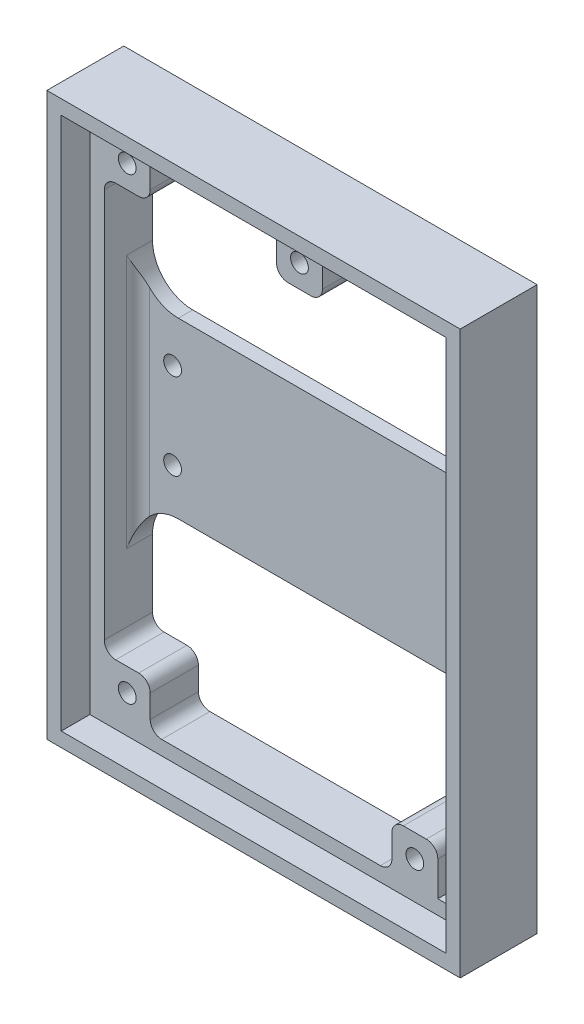
SolidWorks part; units mm, degrees
ref_plane "Plan de face" through (0, 0, 0) normal (0, 0, 1) x (1, 0, 0)
ref_plane "Plan de dessus" through (0, 0, 0) normal (0, 1, 0) x (1, 0, 0)
ref_plane "Plan de droite" through (0, 0, 0) normal (1, 0, 0) x (0, 0, -1)
sketch "Esquisse1" plane through (0, 0, 0) normal (0, 0, 1) x (1, 0, 0)
  line L0 (43, -39.95) -> (35.1, -39.95) construction
  line L1 (-15, 39.95) -> (15, 39.95) construction
  line L2 (-15, 39.95) -> (-15, -39.95) construction
  line L3 (-15, -39.95) -> (15, -39.95) construction
  line L4 (15, 39.95) -> (15, -39.95) construction
  line L5 (-15, 39.95) -> (15, -39.95) construction
  line L6 (-15, -39.95) -> (15, 39.95) construction
  line L11 (-19, 43.75) -> (43, 43.75) construction
  line L13 (-19, 43.75) -> (-19, -44.35) construction
  line L14 (-19, -44.35) -> (43, -44.35) construction
  line L15 (43, 43.75) -> (43, -44.35) construction
  line L16 (-19, 35.95) -> (-11, 35.95)
  line L17 (-11, 35.95) -> (-11, 43.95)
  line L18 (-11, 43.95) -> (11, 43.95)
  line L19 (11, 43.95) -> (11, 35.95)
  line L20 (11, 35.95) -> (19, 35.95)
  line L21 (19, 35.95) -> (19, 43.95)
  line L22 (19, 43.95) -> (43, 43.95)
  line L23 (43, 43.95) -> (43, -43.95)
  line L24 (43, -43.95) -> (39.1, -43.95)
  line L25 (39.1, -43.95) -> (39.1, -35.95)
  line L26 (39.1, -35.95) -> (31.1, -35.95)
  line L27 (31.1, -35.95) -> (31.1, -43.95)
  line L28 (31.1, -43.95) -> (-11, -43.95)
  line L29 (-11, -43.95) -> (-11, -35.95)
  line L30 (-11, -35.95) -> (-19, -35.95)
  line L31 (-19, -35.95) -> (-19, 35.95)
  line L32 (-24, 0) -> (-19, 0) construction
  line L33 (-24, 48.95) -> (48, 48.95)
  line L34 (-24, 48.95) -> (-24, -48.95)
  line L35 (-24, -48.95) -> (48, -48.95)
  line L36 (48, 48.95) -> (48, -48.95)
  line L37 (0, 43.95) -> (0, 48.95) construction
  line L38 (43, 0) -> (48, 0) construction
  line L39 (10.05, -43.95) -> (10.05, -48.95) construction
  circle A0 centre (15, 39.95) radius 1.55
  circle A1 centre (-15, 39.95) radius 1.55
  circle A2 centre (-15, -39.95) radius 1.55
  circle A3 centre (35.1, -39.95) radius 1.55
  point P0 (0, 0)
  point P8 (0, 0)
  point P45 (63.8062, 0)
  point P46 (0, 50.074)
  point P47 (-0.2545, 53.6078)
  point P48 (0, 55.5566)
  dimension "D3" = 3.1
  dimension "D4" = 4
  dimension "D6" = 3.8
  dimension "D7" = 4.4
  dimension "D10" = 4
  dimension "D14" = 4
  dimension "D15" = 5
  dimension "D1" = 79.9
  dimension "D2" = 30
  dimension "D5" = 28
  dimension "D8" = 7.9
  dimension "D9" = 4
  dimension "D11" = 8
  dimension "D12" = 4
  dimension "D13" = 4
extrude "Boss.-Extru.1" add sketch "Esquisse1" along normal blind 8.4
sketch "Esquisse2" plane through (0, 0, 0) normal (0, 0, -1) x (-1, 0, 0)
  line L1 (-15, 36.7746) -> (-12.25, 38.3623)
  line L2 (-12.25, 38.3623) -> (-12.25, 41.5377)
  line L3 (-12.25, 41.5377) -> (-15, 43.1254)
  line L4 (-15, 43.1254) -> (-17.75, 41.5377)
  line L5 (-17.75, 41.5377) -> (-17.75, 38.3623)
  line L6 (-17.75, 38.3623) -> (-15, 36.7746)
  line L7 (14.9963, 36.7746) -> (17.7481, 38.3591)
  line L8 (17.7481, 38.3591) -> (17.7519, 41.5345)
  line L9 (17.7519, 41.5345) -> (15.0037, 43.1254)
  line L10 (15.0037, 43.1254) -> (12.2519, 41.5409)
  line L11 (12.2519, 41.5409) -> (12.2481, 38.3655)
  line L12 (12.2481, 38.3655) -> (14.9963, 36.7746)
  line L13 (15, -43.1254) -> (17.75, -41.5377)
  line L14 (17.75, -41.5377) -> (17.75, -38.3623)
  line L15 (17.75, -38.3623) -> (15, -36.7746)
  line L16 (15, -36.7746) -> (12.25, -38.3623)
  line L17 (12.25, -38.3623) -> (12.25, -41.5377)
  line L18 (12.25, -41.5377) -> (15, -43.1254)
  line L19 (-35.1, -43.1254) -> (-32.35, -41.5377)
  line L20 (-32.35, -41.5377) -> (-32.35, -38.3623)
  line L21 (-32.35, -38.3623) -> (-35.1, -36.7746)
  line L22 (-35.1, -36.7746) -> (-37.85, -38.3623)
  line L23 (-37.85, -38.3623) -> (-37.85, -41.5377)
  line L24 (-37.85, -41.5377) -> (-35.1, -43.1254)
  line L25 (15, -35.95) -> (15, -36.7746) construction
  line L27 (-15, 36.7746) -> (-15, 35.95) construction
  line L28 (-19, 35.95) -> (-11, 35.95) construction
  line L29 (19, -35.95) -> (11, -35.95) construction
  line L30 (-35.1, -35.95) -> (-35.1, -36.7746) construction
  line L31 (-31.1, -35.95) -> (-39.1, -35.95) construction
  circle A0 centre (-15, 39.95) radius 2.75 construction
  circle A1 centre (15, 39.95) radius 2.75 construction
  circle A2 centre (15, -39.95) radius 2.75 construction
  circle A3 centre (-35.1, -39.95) radius 2.75 construction
  dimension "D1" = 5.5
extrude "Enlèv. mat.-Extru.1" cut sketch "Esquisse2" against normal blind 2.5
sketch "Esquisse3" plane through (0, 0, 8.4) normal (0, 0, 1) x (1, 0, 0)
  line L9 (-24, 48.95) -> (48, 48.95)
  line L10 (-24, 48.95) -> (-24, -48.95)
  line L11 (-24, -48.95) -> (48, -48.95)
  line L12 (48, 48.95) -> (48, -48.95)
  line L18 (43, 0) -> (45.5, 0) construction
  line L19 (-21.5, 46.45) -> (45.5, 46.45)
  line L20 (-21.5, 46.45) -> (-21.5, -46.45)
  line L21 (-21.5, -46.45) -> (45.5, -46.45)
  line L22 (45.5, 46.45) -> (45.5, -46.45)
  line L23 (43, -43.95) -> (43, 43.95) construction
  line L24 (-21.5, 0) -> (-19, 0) construction
  line L25 (-19, 35.95) -> (-19, -35.95) construction
  line L26 (12, 46.45) -> (12, 48.95) construction
  line L27 (12, -46.45) -> (12, -48.95) construction
  line L28 (-24, -48.95) -> (48, -48.95) construction
  point P23 (0, 0)
  point P24 (12, -46.6825)
  point P25 (0, 0)
  point P26 (12, -48.95)
  dimension "D1" = 2.5
  dimension "D2" = 2.5
  dimension "D3" = 2.5
  dimension "D4" = 2.5
extrude "Boss.-Extru.2" add sketch "Esquisse3" along normal blind 5
sketch "Esquisse4" plane through (0, 0, 0) normal (0, 0, -1) x (-1, 0, 0)
  line L0 (-48, -48.95) -> (-48, 48.95) construction
  line L1 (-48, 15.142) -> (24, 15.142)
  line L2 (-48, 15.142) -> (-48, -15.142)
  line L3 (-48, -15.142) -> (24, -15.142)
  line L4 (24, 15.142) -> (24, -15.142)
  line L5 (24, 48.95) -> (24, -48.95) construction
  line L6 (-12, 48.95) -> (-12, 15.142) construction
  line L7 (-48, 48.95) -> (24, 48.95) construction
  line L8 (-12, -15.142) -> (-12, -48.95) construction
  line L9 (24, -48.95) -> (-48, -48.95) construction
  line L10 (-12, 15.142) -> (-12, -15.142) construction
  line L12 (-37, 7.5) -> (13, 7.5) construction
  line L13 (-37, 7.5) -> (-37, -7.5) construction
  line L14 (-37, -7.5) -> (13, -7.5) construction
  line L15 (13, 7.5) -> (13, -7.5) construction
  line L16 (-37, 7.5) -> (13, -7.5) construction
  line L17 (-37, -7.5) -> (13, 7.5) construction
  circle A0 centre (-37, 7.5) radius 1.55
  circle A1 centre (-37, -7.5) radius 1.55
  circle A2 centre (13, -7.5) radius 1.55
  circle A3 centre (13, 7.5) radius 1.55
  circle A4 centre (15, 39.95) radius 1.55 construction
  point P16 (-12, 0)
  dimension "D1" = 50
  dimension "D2" = 15
extrude "Boss.-Extru.3" add sketch "Esquisse4" against normal blind 2.5
fillet "Congé2" radius 7 4 edges at (-19, 15.142, 1.25) (-19, -15.142, 1.25) (43, -15.142, 1.25) (43, 15.142, 1.25)
fillet "Congé4" radius 2 17 edges at (-19, 0, 2.5) (43, 0, 2.5) (-19, -35.95, 4.2) (-11, -35.95, 4.2) (-11, -43.95, 4.2) (31.1, -43.95, 4.2) (39.1, -35.95, 4.2) (31.1, -35.95, 4.2) (43, -43.95, 4.2) (-11, 35.95, 4.2) (-19, 35.95, 4.2) (-11, 43.95, 4.2) (11, 43.95, 4.2) (11, 35.95, 4.2) (19, 35.95, 4.2) (19, 43.95, 4.2) (43, 43.95, 4.2)
